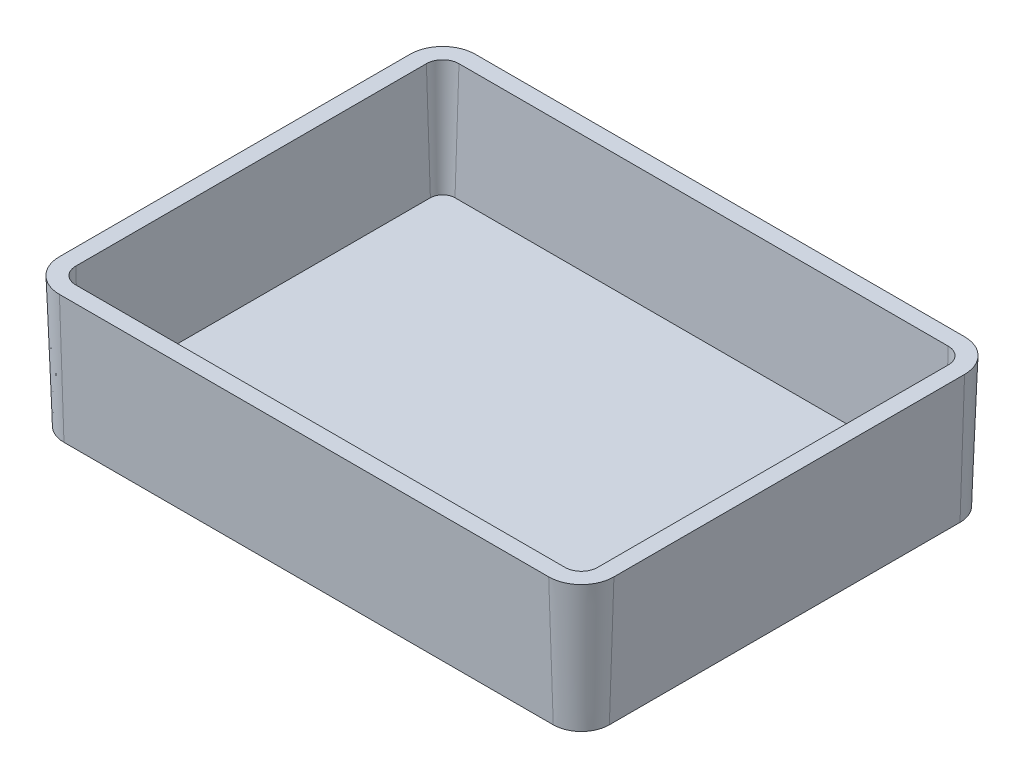
SolidWorks part; units mm, degrees
ref_plane "Front Plane" through (0, 0, 0) normal (0, 0, 1) x (1, 0, 0)
ref_plane "Top Plane" through (0, 0, 0) normal (0, 1, 0) x (1, 0, 0)
ref_plane "Right Plane" through (0, 0, 0) normal (1, 0, 0) x (0, 0, -1)
sketch "Sketch1" plane through (0, 0, 0) normal (0, 1, 0) x (1, 0, 0)
  line L1 (-7.5, -6.375) -> (7.5, -6.375)
  line L2 (-8.5, -5.375) -> (-8.5, 5.375)
  line L3 (-7.5, 6.375) -> (7.5, 6.375)
  line L4 (8.5, -5.375) -> (8.5, 5.375)
  line L5 (-8.5, -6.375) -> (8.5, 6.375) construction
  line L6 (-8.5, 6.375) -> (8.5, -6.375) construction
  arc A0 (-8.5, 5.375) -> (-7.5, 6.375) centre (-7.5, 5.375) cw
  arc A1 (8.5, 5.375) -> (7.5, 6.375) centre (7.5, 5.375) ccw
  arc A2 (8.5, -5.375) -> (7.5, -6.375) centre (7.5, -5.375) cw
  arc A3 (-7.5, -6.375) -> (-8.5, -5.375) centre (-7.5, -5.375) cw
  point P0 (0, 0)
  dimension "D3" = 1
  dimension "D1" = 17
  dimension "D2" = 12.75
extrude "Boss-Extrude1" add sketch "Sketch1" against normal blind 4 draft 2
shell "Shell1" thickness 0.5
